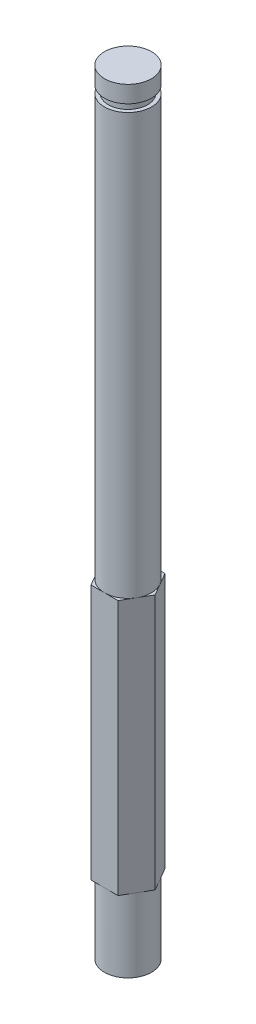
SolidWorks part; units mm, degrees
material "1060 Alloy"
ref_plane "Front Plane" through (0, 0, 0) normal (0, 0, 1) x (1, 0, 0)
ref_plane "Top Plane" through (0, 0, 0) normal (0, 1, 0) x (1, 0, 0)
ref_plane "Right Plane" through (0, 0, 0) normal (1, 0, 0) x (0, 0, -1)
sketch "Sketch1" plane through (0, 0, 0) normal (0, 1, 0) x (1, 0, 0)
  line L1 (1.8331, 3.175) -> (-1.8331, 3.175)
  line L2 (-1.8331, 3.175) -> (-3.6662, 0)
  line L3 (-3.6662, 0) -> (-1.8331, -3.175)
  line L4 (-1.8331, -3.175) -> (1.8331, -3.175)
  line L5 (1.8331, -3.175) -> (3.6662, 0)
  line L6 (3.6662, 0) -> (1.8331, 3.175)
  circle A0 centre (0, 0) radius 3.175 construction
  dimension "D1" = 6.35
extrude "Boss-Extrude1" add sketch "Sketch1" along normal blind 34.544
sketch "Sketch2" plane through (0, 34.544, 0) normal (0, 1, 0) x (1, 0, 0)
  circle A0 centre (0, 0) radius 3.175
extrude "Boss-Extrude2" add sketch "Sketch2" along normal blind 56.896
sketch "Sketch3" plane through (0, 91.44, 0) normal (0, 1, 0) x (1, 0, 0)
  circle A0 centre (0, 0) radius 2.667
  dimension "D1" = 5.334
extrude "Boss-Extrude3" add sketch "Sketch3" along normal blind 1.016
sketch "Sketch4" plane through (0, 92.456, 0) normal (0, 1, 0) x (1, 0, 0)
  circle A0 centre (0, 0) radius 3.175
extrude "Boss-Extrude4" add sketch "Sketch4" along normal blind 2.286
sketch "Sketch5" plane through (0, 0, 0) normal (0, -1, 0) x (1, 0, 0)
  circle A0 centre (0, 0) radius 3.175
extrude "Boss-Extrude5" add sketch "Sketch5" along normal blind 9.906
